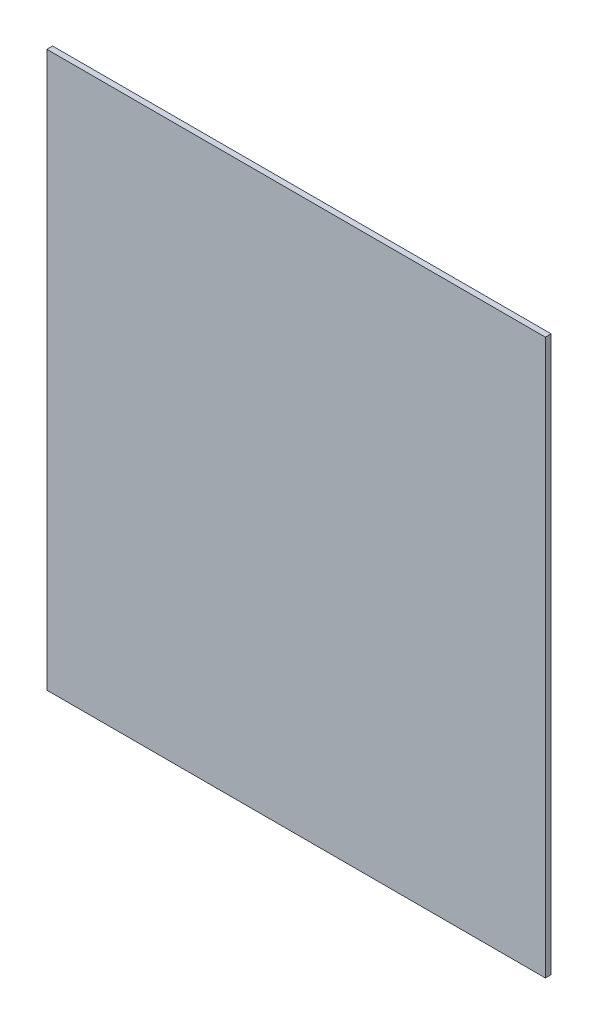
SolidWorks part; units mm, degrees
ref_plane "Alzado" through (0, 0, 0) normal (0, 0, 1) x (1, 0, 0)
ref_plane "Planta" through (0, 0, 0) normal (0, 1, 0) x (1, 0, 0)
ref_plane "Vista lateral" through (0, 0, 0) normal (1, 0, 0) x (0, 0, -1)
sketch "Croquis1" plane through (0, 0, 0) normal (0, 0, 1) x (1, 0, 0)
  line L1 (-116.393, 109.5716) -> (144.107, 109.5716)
  line L2 (-116.393, 109.5716) -> (-116.393, -180.4284)
  line L3 (-116.393, -180.4284) -> (144.107, -180.4284)
  line L4 (144.107, 109.5716) -> (144.107, -180.4284)
  point P4 (13.857, -3.3276)
  dimension "D1" = 260.5
  dimension "D2" = 290
extrude "Saliente-Extruir1" add sketch "Croquis1" along normal blind 3
